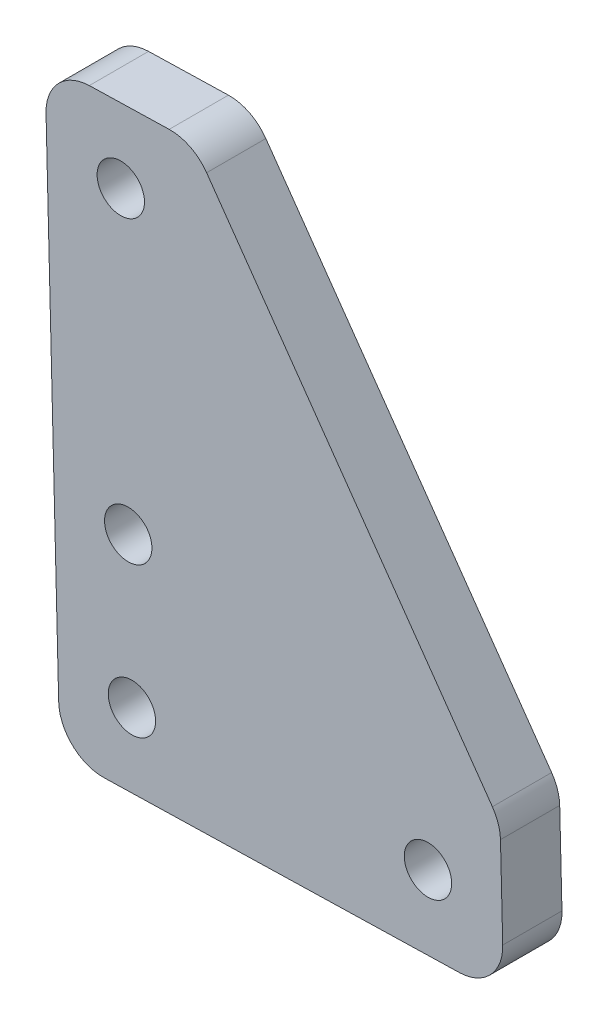
SolidWorks part; units mm, degrees
ref_plane "Front Plane" through (0, 0, 0) normal (0, 0, 1) x (1, 0, 0)
ref_plane "Top Plane" through (0, 0, 0) normal (0, 1, 0) x (1, 0, 0)
ref_plane "Right Plane" through (0, 0, 0) normal (1, 0, 0) x (0, 0, -1)
sketch "Sketch1" plane through (0, 0, 0) normal (0, 0, 1) x (1, 0, 0)
  line L0 (7.988, 36.6307) -> (28.735, 7.1424)
  line B0 (-1.2555, 6.3891) -> (-2.0089, 36.3796)
  line B1 (-1.2555, 6.3891) -> (8.7413, 6.6402)
  line B2 (8.7413, 6.6402) -> (7.988, 36.6307)
  line B3 (-2.0089, 36.3796) -> (7.988, 36.6307)
  line B4 (-1.2555, 6.3891) -> (7.988, 36.6307) construction
  line B5 (8.7413, 6.6402) -> (-2.0089, 36.3796) construction
  circle B6 centre (3.1151, 31.5067) radius 1.6
  circle B7 centre (3.6173, 11.513) radius 1.6
  line B8 (-1.2555, 6.3891) -> (28.735, 7.1424)
  line B9 (-1.2555, 6.3891) -> (-1.0044, -3.6078)
  line B10 (-1.0044, -3.6078) -> (28.9861, -2.8544)
  line B11 (28.735, 7.1424) -> (28.9861, -2.8544)
  line B12 (-1.2555, 6.3891) -> (28.9861, -2.8544) construction
  line B13 (-1.0044, -3.6078) -> (28.735, 7.1424) construction
  circle B14 centre (23.8622, 2.0184) radius 1.6
  circle B15 centre (3.8685, 1.5162) radius 1.6
  dimension "D1" = 90
sketch_block_instance "Block1-1"
sketch_block "Block1" parameters "D1"=10, "D2"=30, "D3"=5, "D4"=20
sketch_block_instance "Block1-3"
extrude "Boss-Extrude1" add sketch "Sketch1" along normal blind 4 contours B3 B0 B1 B2 B7 B6 | B2 B8 L0 | B11 B8 B1 B9 B10 B15 B14
fillet "Fillet2" radius 3 5 edges at (-1.0044, -3.6078, 2) (28.9861, -2.8544, 2) (28.735, 7.1424, 2) (-2.0089, 36.3796, 2) (7.988, 36.6307, 2)
